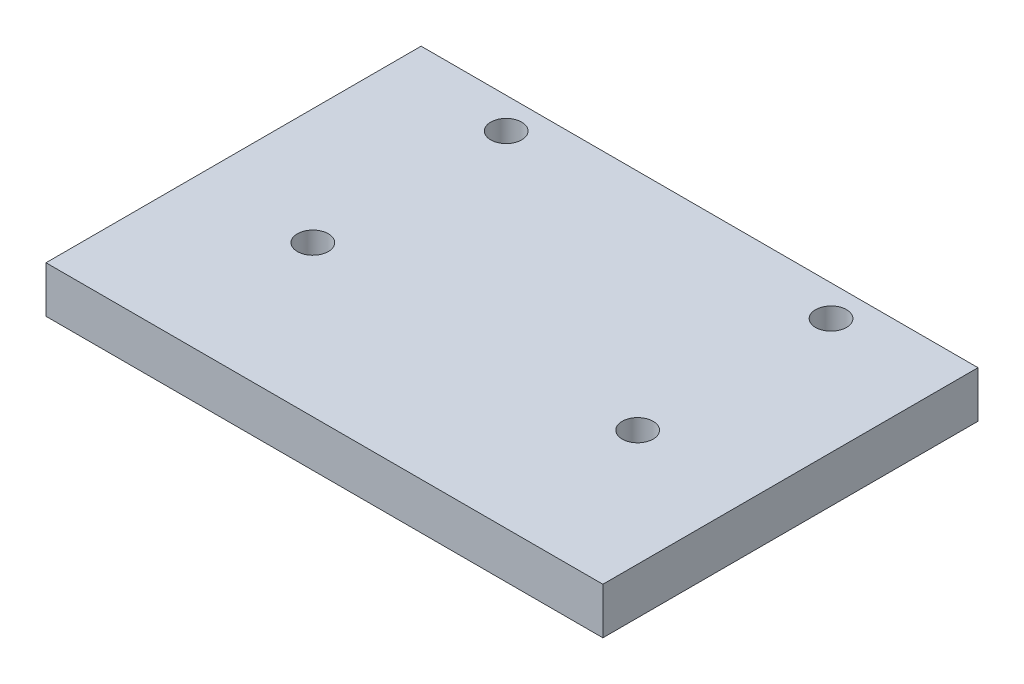
SolidWorks part; units mm, degrees
ref_plane "Front Plane" through (0, 0, 0) normal (0, 0, 1) x (1, 0, 0)
ref_plane "Top Plane" through (0, 0, 0) normal (0, 1, 0) x (1, 0, 0)
ref_plane "Right Plane" through (0, 0, 0) normal (1, 0, 0) x (0, 0, -1)
sketch "Sketch2" plane through (0, 0, 0) normal (0, 1, 0) x (1, 0, 0)
  line L0 (0, 0) -> (0, 24.25)
  line L1 (0, 24.25) -> (36, 24.25)
  line L2 (36, 24.25) -> (36, 0)
  line L3 (36, 0) -> (0, 0)
  line L4 (7.5, 22.25) -> (28.5, 22.25) construction
  circle A0 centre (7.5, 22.25) radius 1
  circle A1 centre (28.5, 22.25) radius 1
  circle A2 centre (28.5, 9.75) radius 1
  circle A3 centre (7.5, 9.75) radius 1
  point P13 (18, 22.25)
  point P14 (18, 24.25)
  dimension "D3" = 2
  dimension "D4" = 2
  dimension "D5" = 2
  dimension "D6" = 2
  dimension "D1" = 36
  dimension "D2" = 24.25
  dimension "D7" = 12.5
  dimension "D8" = 21
  dimension "D9" = 2
extrude "Boss-Extrude1" add sketch "Sketch2" along normal blind 3
